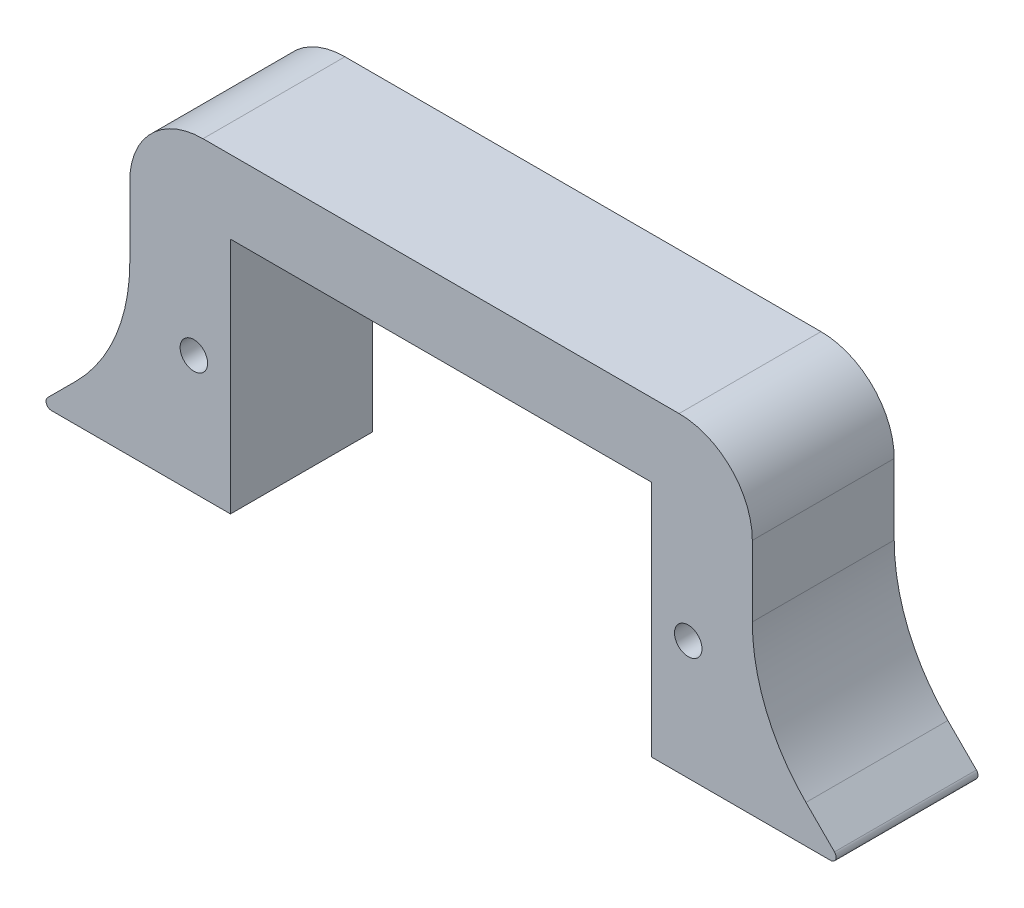
SolidWorks part; units mm, degrees
ref_plane "Front Plane" through (0, 0, 0) normal (0, 0, 1) x (1, 0, 0)
ref_plane "Top Plane" through (0, 0, 0) normal (0, 1, 0) x (1, 0, 0)
ref_plane "Right Plane" through (0, 0, 0) normal (1, 0, 0) x (0, 0, -1)
sketch "Sketch1" plane through (0, 0, 0) normal (0, 0, 1) x (1, 0, 0)
  line L0 (-11.5, -6.5) -> (-17, -6.5)
  line L1 (-11.5, -6.5) -> (11.5, -6.5)
  line L2 (-11.5, -6.5) -> (-11.5, 6.5)
  line L3 (-11.5, 6.5) -> (11.5, 6.5)
  line L4 (11.5, -6.5) -> (11.5, 6.5)
  line L5 (-11.5, -6.5) -> (11.5, 6.5) construction
  line L6 (-11.5, 6.5) -> (11.5, -6.5) construction
  line L7 (-17, -6.5) -> (-17, 10.5)
  line L8 (-17, 10.5) -> (17, 10.5)
  line L9 (11.5, -6.5) -> (17, -6.5)
  line L10 (17, -6.5) -> (17, 10.5)
  point P0 (0, 0)
  dimension "D1" = 13
  dimension "D2" = 23
  dimension "D3" = 5.5
  dimension "D4" = 5.5
  dimension "D5" = 4
extrude "Boss-Extrude1" add sketch "Sketch1" along normal blind 7.75 contours L9 L10 L8 L7 L0 L2 L3 L4
sketch "Sketch2" plane through (0, 0, 7.75) normal (0, 0, 1) x (1, 0, 0)
  line L0 (0, 0) -> (-17, 0) construction
  line L1 (-17, -6.5) -> (-17, 10.5) construction
  line L2 (0, 0) -> (17, 0) construction
  line L3 (17, -6.5) -> (17, 10.5) construction
  line L4 (0, 0) -> (0, 6.5) construction
  line L5 (-11.5, 6.5) -> (11.5, 6.5) construction
  circle A0 centre (-13.5, 0) radius 0.75
  circle A1 centre (13.5, 0) radius 0.75
  dimension "D1" = 1.5
  dimension "D2" = 13.5
extrude "Cut-Extrude1" cut sketch "Sketch2" against normal through all
sketch "Sketch3" plane through (0, 0, 0) normal (0, 0, 1) x (1, 0, 0)
  line L0 (0, 0) -> (0, 6.5) construction
  line L1 (-11.5, 6.5) -> (11.5, 6.5) construction
  line L2 (-17, -1.5) -> (-22, -6.5)
  line L3 (-17, -6.5) -> (-17, 10.5) construction
  line L4 (-22, -6.5) -> (-17, -6.5)
  line L5 (-17, -1.5) -> (-17, -6.5)
  line L6 (17, -1.5) -> (22, -6.5)
  line L7 (22, -6.5) -> (17, -6.5)
  line L8 (17, -1.5) -> (17, -6.5)
  dimension "D1" = 5
  dimension "D2" = 5
extrude "Boss-Extrude2" add sketch "Sketch3" along normal blind 7.75
sketch "Sketch4" plane through (0, -6.5, 0) normal (0, -1, 0) x (1, 0, 0)
  line L0 (-11.5, 3.875) -> (11.5, 3.875) construction
  line L1 (-11.5, 7.75) -> (-11.5, 0) construction
  line L2 (11.5, 7.75) -> (11.5, 0) construction
  line L3 (22, 3.875) -> (11.5, 3.875) construction
  line L4 (22, 7.75) -> (22, 0) construction
  line L5 (-11.5, 3.875) -> (-22, 3.875) construction
  line L6 (-22, 7.75) -> (-22, 0) construction
  line L7 (0, 3.875) -> (0, 0) construction
  circle A0 centre (-16.75, 3.875) radius 0.75
  circle A1 centre (16.75, 3.875) radius 0.75
  dimension "D1" = 1.5
extrude "Cut-Extrude2" cut sketch "Sketch4" against normal blind 2
fillet "Fillet1" radius 10 2 edges at (17, -1.5, 3.875) (-17, -1.5, 3.875)
fillet "Fillet2" radius 4 2 edges at (-17, 10.5, 3.875) (17, 10.5, 3.875)
fillet "Fillet3" radius 0.3 2 edges at (22, -6.5, 3.875) (-22, -6.5, 3.875)
